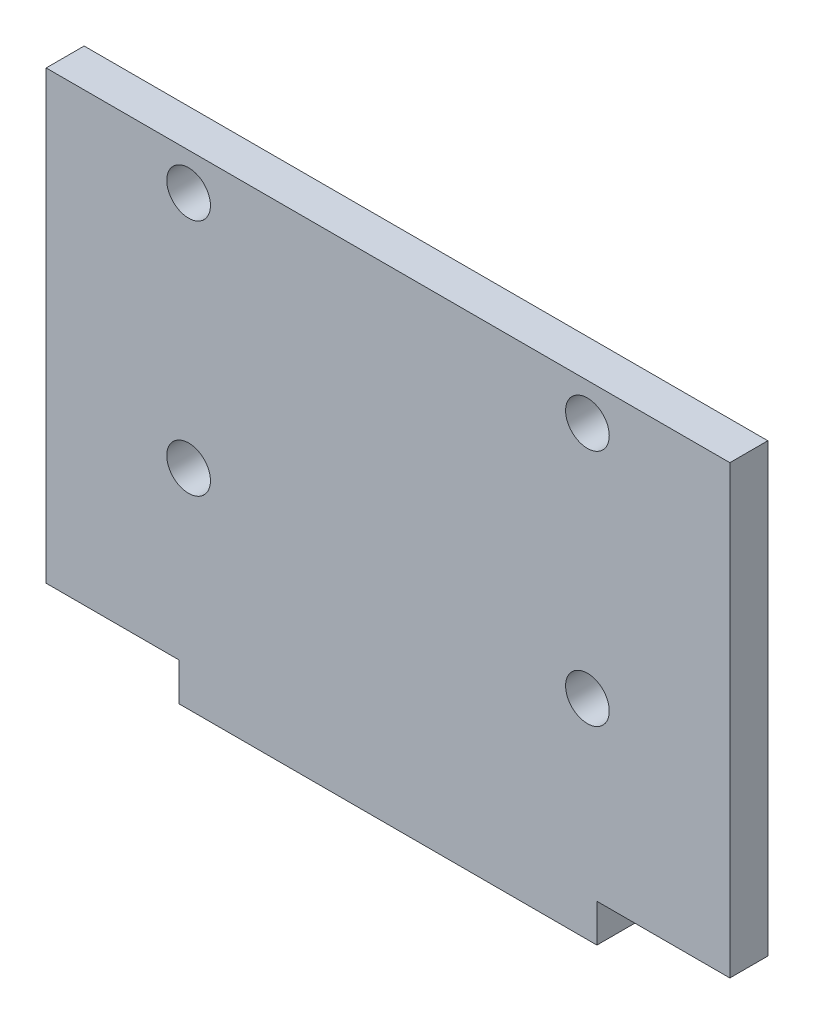
SolidWorks part; units mm, degrees
ref_plane "Front Plane" through (0, 0, 0) normal (0, 0, 1) x (1, 0, 0)
ref_plane "Top Plane" through (0, 0, 0) normal (0, 1, 0) x (1, 0, 0)
ref_plane "Right Plane" through (0, 0, 0) normal (1, 0, 0) x (0, 0, -1)
sketch "Sketch1" plane through (0, 0, 0) normal (0, 0, 1) x (1, 0, 0)
  line L0 (-7, 2) -> (-7, 25.5)
  line L5 (-7, 25.5) -> (29, 25.5)
  line L8 (29, 25.5) -> (29, 2)
  line L9 (29, 2) -> (22, 2)
  line L12 (22, 2) -> (22, 0)
  line L13 (22, 0) -> (0, 0)
  line L14 (0, 0) -> (0, 2)
  line L17 (0, 2) -> (-7, 2)
  circle A0 centre (0.5, 11) radius 1.15
  circle A1 centre (0.5, 23.55) radius 1.15
  circle A2 centre (21.5, 23.55) radius 1.15
  circle A3 centre (21.5, 11) radius 1.15
  point P1 (0, 0)
  point P2 (-7.0025, 25.4953)
  point P3 (-7.0025, 25.3989)
  point P4 (29.0053, 25.4953)
  point P5 (28.8937, 25.4953)
  point P6 (0, 0)
  point P7 (0, 1.9953)
  point P8 (-0.0833, 1.9953)
  point P9 (22.0299, 1.9953)
  point P11 (22.0885, 1.9953)
  point P12 (0, 0)
  point P13 (0, 0)
  point P14 (0, 0)
  point P15 (0, 0)
  point P17 (0, 0)
  point P19 (0, 0)
  point P20 (0, 0)
  point P22 (0, 0)
  point P23 (0, 0)
  point P25 (0, 0)
  point P27 (0, 0)
  dimension "D8" = 2.3
  dimension "D1" = 2
  dimension "D2" = 25.5
  dimension "D3" = 22
  dimension "D4" = 7.5
  dimension "D5" = 9
  dimension "D6" = 12.55
  dimension "D7" = 21
  dimension "D9" = 36
  dimension "D10" = 7
extrude "Boss-Extrude1" add sketch "Sketch1" along normal blind 2
